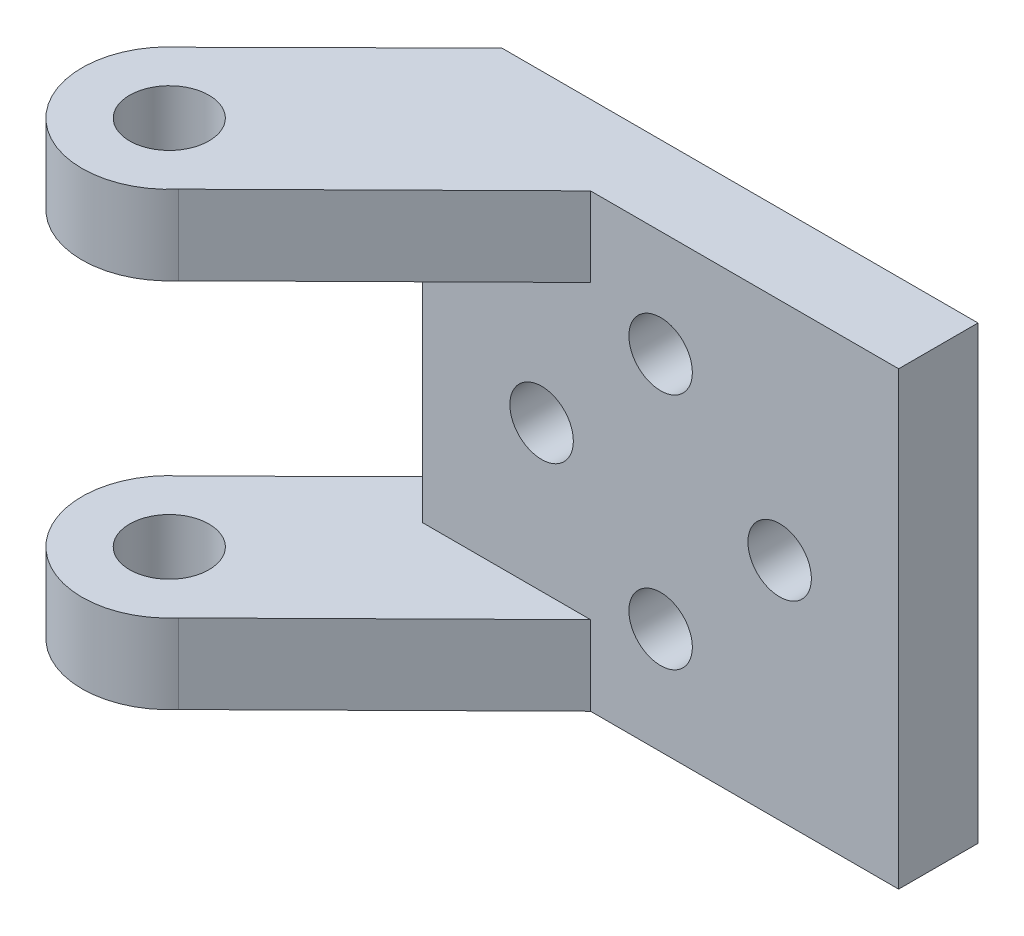
SolidWorks part; units mm, degrees
ref_plane "Front Plane" through (0, 0, 0) normal (0, 0, 1) x (1, 0, 0)
ref_plane "Top Plane" through (0, 0, 0) normal (0, 1, 0) x (1, 0, 0)
ref_plane "Right Plane" through (0, 0, 0) normal (1, 0, 0) x (0, 0, -1)
sketch "Sketch2" plane through (0, 0, 0) normal (0, -1, 0) x (1, 0, 0)
  circle A0 centre (0, 0) radius 4
extrude "Boss-Extrude2" add sketch "Sketch2" along normal blind 5
sketch "Sketch3" plane through (0, -5, 0) normal (0, -1, 0) x (1, 0, 0)
  line L0 (-3.7303, -1.444) -> (3.7518, 1.3878)
  line L1 (0, -11.3) -> (36.6614, -11.3)
  line L2 (0, -11.3) -> (-3.7303, -1.444)
  line L3 (6.6614, -6.3) -> (36.6614, -6.3)
  line L4 (36.6614, -11.3) -> (36.6614, -6.3)
  line L5 (6.6614, -6.3) -> (3.7518, 1.3878)
  line L7 (0, -6.3) -> (36.6614, -6.3) construction
  circle A0 centre (0, 0) radius 4 construction
  circle A2 centre (0, 0) radius 2.5 construction
  circle A3 centre (0, 0) radius 2.5
  point P9 (7.482, -8.4682)
  dimension "D1" = 5
extrude "Boss-Extrude3" add sketch "Sketch3" against normal blind 5
sketch "Sketch5" plane through (0, 0, -6.3) normal (0, 0, 1) x (1, 0, 0)
  line L0 (21.6614, -2.5) -> (36.6614, -2.5)
  line L3 (21.6614, 0) -> (21.6614, -5)
  line L4 (6.6614, 0) -> (36.6614, 0) construction
  line L5 (6.6614, -5) -> (36.6614, -5) construction
  line L7 (36.6614, 0) -> (36.6614, -5) construction
  circle A0 centre (29.1614, -2.5) radius 1.7
  circle A1 centre (14.1614, -2.5) radius 1.7
extrude "Cut-Extrude1" cut sketch "Sketch5" against normal through all contours A1 | L0 A0 | L0 A0
sketch "Sketch6" plane through (0, -5, 0) normal (0, -1, 0) x (1, 0, 0)
  line L0 (36.6614, -11.3) -> (36.6614, -6.3) construction
  line L1 (0, -11.3) -> (36.6614, -11.3)
  line L3 (-1.1354, -8.3) -> (36.6614, -8.3)
  line L4 (36.6614, -11.3) -> (36.6614, -8.3)
  line L5 (0, -11.3) -> (-3.7303, -1.444) construction
  line L6 (0, -11.3) -> (-3.7303, -1.444)
  line M3 (-3.7303, -1.444) -> (0, -11.3)
  line M4 (0, -11.3) -> (36.6614, -11.3)
  line M5 (36.6614, -11.3) -> (36.6614, -6.3)
extrude "Boss-Extrude4" add sketch "Sketch6" along normal blind 5 contours L3 M3 M4 M5
sketch "Sketch7" plane through (0, 0, -8.3) normal (0, 0, 1) x (1, 0, 0)
  line L0 (14.1614, -2.5) -> (29.1614, -2.5)
  line L1 (-1.1354, -7.5) -> (36.6614, -7.5)
  line L2 (-1.1354, -10) -> (-1.1354, -5) construction
  line L3 (36.6614, -10) -> (36.6614, -5) construction
  line L4 (21.6614, -2.5) -> (21.6614, -7.5)
  circle A0 centre (21.6614, -7.5) radius 1.7
extrude "Cut-Extrude2" cut sketch "Sketch7" against normal through all contours A0
sketch "Sketch9" plane through (0, 0, -6.3) normal (0, 0, 1) x (1, 0, 0)
  line L1 (36.6614, 0) -> (6.6614, 0)
  line L2 (36.6614, 0) -> (36.6614, 9.2)
  line L3 (36.6614, 9.2) -> (6.6614, 9.2)
  line L4 (6.6614, 0) -> (6.6614, 9.2)
extrude "Boss-Extrude5" add sketch "Sketch9" against normal up to surface (5 mm away) up to face at (23.3614, -7.5, -11.3)
mirror "Mirror1" about plane through (36.6614, 9.2, -42.679) normal (0, 1, 0) of bodies 107
sketch "Sketch10" plane through (0, 0, -8.3) normal (0, 0, 1) x (1, 0, 0)
  line L4 (-1.1354, 23.4) -> (36.6614, 23.4)
  line L5 (36.6614, 23.4) -> (36.6614, 28.4)
  line L6 (36.6614, 28.4) -> (-1.1354, 28.4)
  line L7 (-1.1354, 28.4) -> (-1.1354, 23.4)
  line L8 (-1.1354, 23.4) -> (36.6614, 23.4)
  line L9 (36.6614, 23.4) -> (36.6614, 28.4)
  line L10 (36.6614, 28.4) -> (-1.1354, 28.4)
  line L11 (-1.1354, 28.4) -> (-1.1354, 23.4)
  line L12 (36.6614, -5) -> (-1.1354, -5)
  line L13 (-1.1354, -5) -> (-1.1354, -10)
  line L14 (-1.1354, -10) -> (36.6614, -10)
  line L15 (36.6614, -10) -> (36.6614, -5)
  line L16 (36.6614, -5) -> (-1.1354, -5)
  line L17 (-1.1354, -5) -> (-1.1354, -10)
  line L18 (-1.1354, -10) -> (36.6614, -10)
  line L19 (36.6614, -10) -> (36.6614, -5)
  dimension "D1" = 0
  dimension "D2" = 0
extrude "Cut-Extrude3" cut sketch "Sketch10" against normal through all
sketch "Sketch11" plane through (0, 0, -6.3) normal (0, 0, 1) x (1, 0, 0)
  line L6 (6.6614, -5) -> (36.6614, -5)
  line L7 (36.6614, -5) -> (36.6614, 23.4)
  line L8 (36.6614, 23.4) -> (6.6614, 23.4)
  line L9 (6.6614, 23.4) -> (6.6614, 18.4)
  line L10 (6.6614, 18.4) -> (6.6614, 0)
  line L11 (6.6614, 0) -> (6.6614, -5)
  line L12 (6.6614, -5) -> (36.6614, -5)
  line L13 (36.6614, -5) -> (36.6614, 23.4)
  line L14 (36.6614, 23.4) -> (6.6614, 23.4)
  line L15 (6.6614, 23.4) -> (6.6614, 18.4)
  line L16 (6.6614, 18.4) -> (6.6614, 0)
  line L17 (6.6614, 0) -> (6.6614, -5)
  dimension "D1" = 0
extrude "Boss-Extrude6" add sketch "Sketch11" against normal up to surface (5 mm away) up to face at (10.8307, 9.2, -11.3)
sketch "Sketch13" plane through (0, -5, 0) normal (0, -1, 0) x (1, 0, 0)
  line L0 (6.6614, -6.3) -> (6.6614, -11.3)
  line L1 (36.6614, -11.3) -> (0, -11.3) construction
  line L3 (6.6614, -11.3) -> (-7.3785, -11.3)
  line L4 (6.6614, -11.3) -> (6.6614, 8.3184)
  line L5 (6.6614, 8.3184) -> (-7.3785, 8.3184)
  line L6 (-7.3785, -11.3) -> (-7.3785, 8.3184)
extrude "Cut-Extrude5" cut sketch "Sketch13" against normal through all
sketch "Sketch14" plane through (0, -5, 0) normal (0, -1, 0) x (1, 0, 0)
  line L1 (0, 0) -> (0, 3)
  line L2 (6.6614, -11.3) -> (-3.4606, -1.2748)
  line L5 (6.6614, -6.3) -> (17.2448, -6.3)
  line L6 (17.2448, -6.3) -> (4.1752, 6.5801)
  line L8 (6.6614, -6.3) -> (6.6614, -11.3)
  line L9 (6.6614, -11.3) -> (36.6614, -11.3)
  line L10 (36.6614, -11.3) -> (36.6614, -6.3)
  line L11 (36.6614, -6.3) -> (6.6614, -6.3)
  line L12 (6.6614, -6.3) -> (6.6614, -11.3)
  circle A2 centre (0, 3) radius 2.5
  circle A3 centre (0, 3) radius 5.5
  dimension "D1" = 3
  dimension "D3" = 0
extrude "Boss-Extrude7" add sketch "Sketch14" against normal blind 5
sketch "Sketch15" plane through (0, 23.4, 0) normal (0, 1, 0) x (1, 0, 0)
  line L8 (4.1752, -6.5801) -> (17.2448, 6.3)
  line L9 (17.2448, 6.3) -> (6.6614, 6.3)
  line L10 (6.6614, 6.3) -> (6.6614, 11.3)
  line L11 (6.6614, 11.3) -> (-3.4606, 1.2748)
  line L12 (4.1752, -6.5801) -> (17.2448, 6.3)
  line L13 (17.2448, 6.3) -> (6.6614, 6.3)
  line L14 (6.6614, 6.3) -> (6.6614, 11.3)
  line L15 (6.6614, 11.3) -> (-3.4606, 1.2748)
  circle A1 centre (0, -3) radius 2.5 construction
  arc A2 (-3.4606, 1.2748) -> (4.1752, -6.5801) centre (0, -3) ccw
  arc A3 (-3.4606, 1.2748) -> (4.1752, -6.5801) centre (0, -3) ccw
  circle A4 centre (0, -3) radius 2.5
  dimension "D1" = 0
extrude "Boss-Extrude8" add sketch "Sketch15" against normal blind 5
sketch "Sketch17" plane through (0, 0, -6.3) normal (0, 0, 1) x (1, 0, 0)
  line L0 (21.6614, 9.2) -> (21.6614, 23.4)
  line L1 (17.2448, 23.4) -> (36.6614, 23.4) construction
  line L2 (21.6614, 9.2) -> (6.6614, 9.2)
  line L3 (6.6614, 18.4) -> (6.6614, 0) construction
  circle A0 centre (14.1614, 9.2) radius 2
  circle A1 centre (21.6614, 16.7) radius 2
  circle A2 centre (29.1614, 9.2) radius 2
  circle A3 centre (21.6614, 1.7) radius 2
  point P18 (21.6614, 9.2)
  dimension "D1" = 4
extrude "Cut-Extrude6" cut sketch "Sketch17" against normal through all contours A3 | A1 | A2 | A0
sketch "Sketch18" plane through (0, 23.4, 0) normal (0, 1, 0) x (1, 0, 0)
  line L5 (36.6614, 11.3) -> (6.6614, 11.3)
  line L6 (6.6614, 11.3) -> (-3.4606, 1.2748)
  line L7 (4.1752, -6.5801) -> (17.2448, 6.3)
  line L8 (17.2448, 6.3) -> (36.6614, 6.3)
  line L9 (36.6614, 6.3) -> (36.6614, 11.3)
  line L10 (36.6614, 11.3) -> (6.6614, 11.3)
  line L11 (6.6614, 11.3) -> (-3.4606, 1.2748)
  line L12 (4.1752, -6.5801) -> (17.2448, 6.3)
  line L13 (17.2448, 6.3) -> (36.6614, 6.3)
  line L14 (36.6614, 6.3) -> (36.6614, 11.3)
  circle A0 centre (0, -3) radius 2.5 construction
  arc A1 (-3.4606, 1.2748) -> (4.1752, -6.5801) centre (0, -3) ccw
  arc A2 (-3.4606, 1.2748) -> (4.1752, -6.5801) centre (0, -3) ccw
  circle A3 centre (0, -3) radius 2.5
  dimension "D1" = 0
sketch "Sketch19" plane through (0, 0, -11.3) normal (0, 0, -1) x (-1, 0, 0)
  line L12 (-6.6614, 18.4) -> (-6.6614, 23.4)
  line L13 (-6.6614, 23.4) -> (-36.6614, 23.4)
  line L14 (-36.6614, 23.4) -> (-36.6614, -5)
  line L15 (-36.6614, -5) -> (-6.6614, -5)
  line L16 (-6.6614, -5) -> (-6.6614, 0)
  line L17 (-6.6614, 0) -> (-6.6614, 18.4)
  line L18 (-6.6614, 18.4) -> (-6.6614, 23.4)
  line L19 (-6.6614, 23.4) -> (-36.6614, 23.4)
  line L20 (-36.6614, 23.4) -> (-36.6614, -5)
  line L21 (-36.6614, -5) -> (-6.6614, -5)
  line L22 (-6.6614, -5) -> (-6.6614, 0)
  line L23 (-6.6614, 0) -> (-6.6614, 18.4)
  circle A1 centre (-14.1614, 9.2) radius 2
  circle A2 centre (-14.1614, 9.2) radius 2
  circle A3 centre (-29.1614, 9.2) radius 2
  circle A4 centre (-29.1614, 9.2) radius 2
  circle A5 centre (-21.6614, 16.7) radius 2
  circle A6 centre (-21.6614, 16.7) radius 2
  circle A7 centre (-21.6614, 1.7) radius 2
  circle A8 centre (-21.6614, 1.7) radius 2
  dimension "D1" = 0
  dimension "D2" = 0
  dimension "D3" = 0
  dimension "D4" = 0
  dimension "D5" = 0
